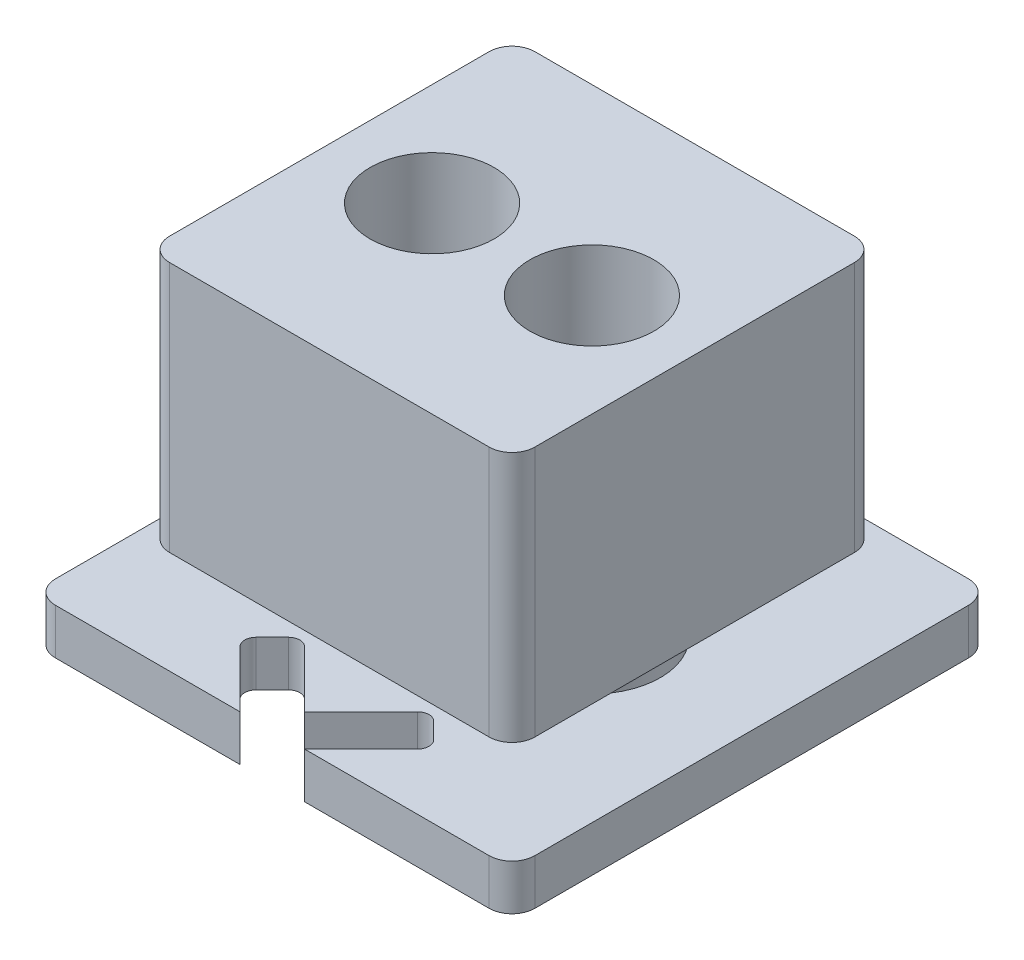
SolidWorks part; units mm, degrees
ref_plane "Front Plane" through (0, 0, 0) normal (0, 0, 1) x (1, 0, 0)
ref_plane "Top Plane" through (0, 0, 0) normal (0, 1, 0) x (1, 0, 0)
ref_plane "Right Plane" through (0, 0, 0) normal (1, 0, 0) x (0, 0, -1)
sketch "Sketch1" plane through (0, 0, 0) normal (0, 1, 0) x (1, 0, 0)
  line L1 (-8, -8) -> (8, -8)
  line L2 (-8, -8) -> (-8, 8)
  line L3 (-8, 8) -> (8, 8)
  line L4 (8, -8) -> (8, 8)
  line L5 (-8, -8) -> (8, 8) construction
  line L6 (-8, 8) -> (8, -8) construction
  point P0 (0, 0)
  dimension "D1" = 16
  dimension "D2" = 16
extrude "Boss-Extrude1" add sketch "Sketch1" along normal blind 11
fillet "Fillet1" radius 1 4 edges at (-8, 5.5, -8) (-8, 5.5, 8) (8, 5.5, -8) (8, 5.5, 8)
sketch "Sketch2" plane through (0, 11, 0) normal (0, 1, 0) x (1, 0, 0)
  line L0 (-2.825, 0) -> (2.825, 0) construction
  line L2 (-4.475, -1.65) -> (-1.175, -1.65)
  line L3 (-4.475, -1.65) -> (-4.475, 1.65)
  line L4 (-4.475, 1.65) -> (-1.175, 1.65)
  line L5 (-1.175, -1.65) -> (-1.175, 1.65)
  line L6 (-4.475, -1.65) -> (-1.175, 1.65) construction
  line L7 (-4.475, 1.65) -> (-1.175, -1.65) construction
  line L8 (1.175, -1.65) -> (4.475, -1.65)
  line L9 (1.175, -1.65) -> (1.175, 1.65)
  line L10 (1.175, 1.65) -> (4.475, 1.65)
  line L11 (4.475, -1.65) -> (4.475, 1.65)
  line L12 (1.175, -1.65) -> (4.475, 1.65) construction
  line L13 (1.175, 1.65) -> (4.475, -1.65) construction
  point P4 (0, 0)
  dimension "D1" = 3.3
  dimension "D2" = 3.3
  dimension "D3" = 3.3
  dimension "D4" = 3.3
  dimension "D5" = 5.65
extrude "Cut-Extrude1" [suppressed] cut sketch "Sketch2" against normal blind 2
sketch "Sketch4" plane through (0, 0, 0) normal (0, -1, 0) x (-1, 0, 0)
  line L0 (3.5, 0) -> (-3.5, 0) construction
  circle A0 centre (3.5, 0) radius 3
  circle A1 centre (-3.5, 0) radius 3
  point P8 (0, 0)
  dimension "D1" = 7
  dimension "D2" = 6
  dimension "D3" = 6
extrude "Boss-Extrude2" add sketch "Sketch4" along normal blind 4
sketch "Sketch5" plane through (0, -4, 0) normal (0, -1, 0) x (-1, 0, 0)
  line L1 (9.5, 10.5) -> (-9.5, 10.5)
  line L2 (10.5, 9.5) -> (10.5, -9.5)
  line L3 (9.5, -10.5) -> (-9.5, -10.5)
  line L4 (-10.5, 9.5) -> (-10.5, -9.5)
  line L5 (10.5, 10.5) -> (-10.5, -10.5) construction
  line L6 (10.5, -10.5) -> (-10.5, 10.5) construction
  arc A0 (10.5, -9.5) -> (9.5, -10.5) centre (9.5, -9.5) cw
  arc A1 (-10.5, -9.5) -> (-9.5, -10.5) centre (-9.5, -9.5) ccw
  arc A2 (-9.5, 10.5) -> (-10.5, 9.5) centre (-9.5, 9.5) ccw
  arc A3 (9.5, 10.5) -> (10.5, 9.5) centre (9.5, 9.5) cw
  point P0 (0, 0)
  dimension "D3" = 1
  dimension "D1" = 21
  dimension "D2" = 21
extrude "Boss-Extrude3" add sketch "Sketch5" against normal blind 2
sketch "Sketch3" plane through (0, 11, 0) normal (0, 1, 0) x (1, 0, 0)
  line L0 (-3.5, 0) -> (3.5, 0) construction
  circle A0 centre (-3.5, 0) radius 2.715
  circle A1 centre (3.5, 0) radius 2.715
  point P8 (0, 0)
  dimension "D2" = 5.43
  dimension "D3" = 5.43
  dimension "D1" = 7
extrude "Cut-Extrude2" cut sketch "Sketch3" against normal through all
sketch "Sketch7" plane through (0, -2, 0) normal (0, 1, 0) x (1, 0, 0)
  line L0 (9.5, -10.5) -> (-9.5, -10.5) construction
  line L1 (2.8284, -14.7426) -> (4.2426, -13.3284)
  line L2 (2.8284, -14.7426) -> (-3.8891, -8.0251)
  line L3 (-3.8891, -7.318) -> (-3.182, -6.6109)
  line L4 (4.2426, -13.3284) -> (-2.4749, -6.6109)
  line L5 (2.8284, -14.7426) -> (-2.8284, -6.2574) construction
  line L6 (-4.2426, -7.6716) -> (4.2426, -13.3284) construction
  line L8 (-4.2426, -13.3284) -> (-2.8284, -14.7426)
  line L9 (-4.2426, -13.3284) -> (2.4749, -6.6109)
  line L10 (3.182, -6.6109) -> (3.8891, -7.318)
  line L11 (-2.8284, -14.7426) -> (3.8891, -8.0251)
  line L12 (-4.2426, -13.3284) -> (4.2426, -7.6716) construction
  line L13 (2.8284, -6.2574) -> (-2.8284, -14.7426) construction
  arc A0 (-2.4749, -6.6109) -> (-3.182, -6.6109) centre (-2.8284, -6.9645) ccw
  arc A1 (3.8891, -7.318) -> (3.8891, -8.0251) centre (3.5355, -7.6716) cw
  arc A2 (3.182, -6.6109) -> (2.4749, -6.6109) centre (2.8284, -6.9645) ccw
  arc A3 (-3.8891, -7.318) -> (-3.8891, -8.0251) centre (-3.5355, -7.6716) ccw
  point P0 (0, -10.5)
  point P7 (0, -10.5)
  point P12 (-1.4142, -10.5)
  point P13 (1.4142, -10.5)
  line M12 (-9.5, -10.5) -> (9.5, -10.5)
  dimension "D7" = 0.5
  dimension "D8" = 0.5
  dimension "D1" = 2
  dimension "D2" = 45
  dimension "D3" = 2
  dimension "D4" = 45
  dimension "D5" = 4
  dimension "D6" = 4
extrude "Cut-Extrude3" cut sketch "Sketch7" against normal through all contours L10 A2 L9 L4 L11 A1 | L3 A3 L2 L9 L4 A0 | L9 L4 M12
equation "\"D2@Sketch2\"=\"D1@Sketch2\""
equation "\"D3@Sketch2\"=\"D1@Sketch2\""
equation "\"D4@Sketch2\"=\"D1@Sketch2\""
equation "\"D2@Sketch1\"=\"D1@Sketch1\""
equation "\"D3@Sketch3\"=\"D2@Sketch3\""
equation "\"D3@Sketch4\"=\"D2@Sketch4\""
equation "\"D2@Sketch5\"=\"D1@Sketch5\""
equation "\"D3@Sketch7\"=\"D1@Sketch7\""
equation "\"D6@Sketch7\"=\"D5@Sketch7\""
